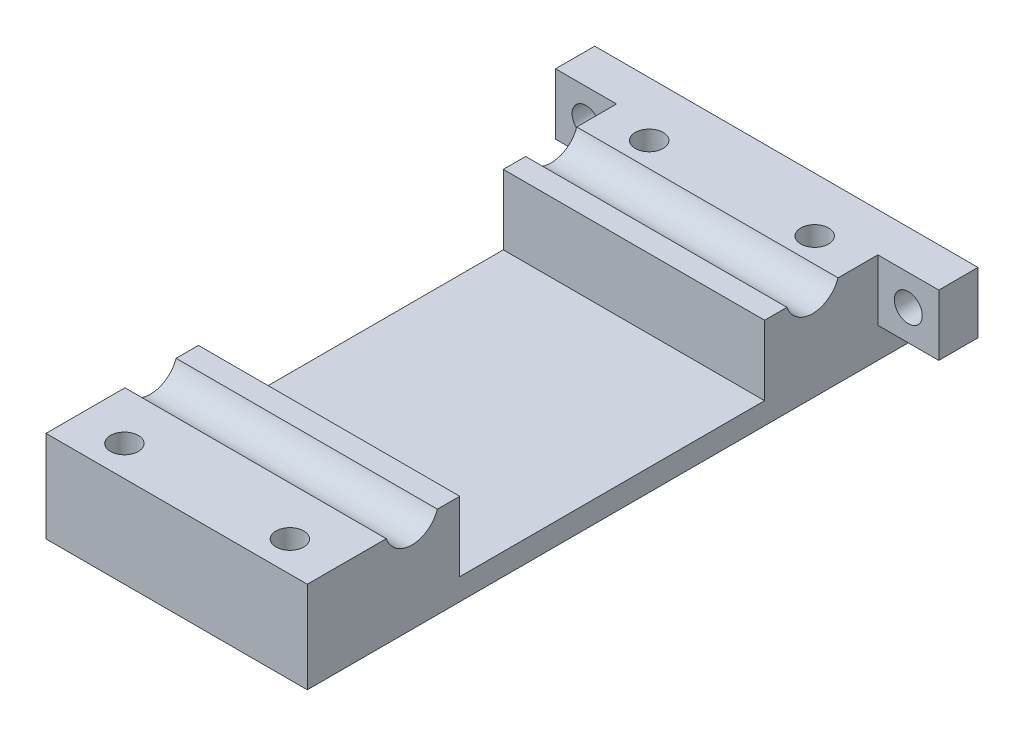
SolidWorks part; units mm, degrees
ref_plane "Front Plane" through (0, 0, 0) normal (0, 0, 1) x (1, 0, 0)
ref_plane "Top Plane" through (0, 0, 0) normal (0, 1, 0) x (1, 0, 0)
ref_plane "Right Plane" through (0, 0, 0) normal (1, 0, 0) x (0, 0, -1)
sketch "Sketch1" plane through (0, 0, 0) normal (0, 1, 0) x (1, 0, 0)
  line L1 (-15, -35) -> (15, -35)
  line L2 (-15, -35) -> (-15, 35)
  line L3 (-15, 35) -> (15, 35)
  line L4 (15, -35) -> (15, 35)
  line L5 (-15, -35) -> (15, 35) construction
  line L6 (-15, 35) -> (15, -35) construction
  point P0 (0, 0)
  dimension "D1" = 30
  dimension "D2" = 70
extrude "Boss-Extrude1" add sketch "Sketch1" along normal blind 10.5
sketch "Sketch2" plane through (0, 10.5, 0) normal (0, 1, 0) x (1, 0, 0)
  line L0 (15, -35) -> (15, 35) construction
  line L1 (-15, -17.5) -> (15, -17.5)
  line L2 (-15, -17.5) -> (-15, 17.5)
  line L3 (-15, 17.5) -> (15, 17.5)
  line L4 (15, -17.5) -> (15, 17.5)
  line L5 (-15, -17.5) -> (15, 17.5) construction
  line L6 (-15, 17.5) -> (15, -17.5) construction
  point P0 (0, 0)
  dimension "D1" = 35
extrude "Cut-Extrude1" cut sketch "Sketch2" against normal blind 8
sketch "Sketch3" plane through (15, 0, 0) normal (1, 0, 0) x (0, 0, -1)
  line L0 (-35, 10.5) -> (-17.5, 10.5) construction
  line L1 (-35, 10.5) -> (-35, 0) construction
  circle A0 centre (-23, 11.5) radius 3.1
  circle A1 centre (23, 11.5) radius 3.1
  point P4 (0, 0)
  dimension "D1" = 6.2
  dimension "D2" = 6.2
  dimension "D3" = 1
  dimension "D4" = 12
  dimension "D5" = 46
extrude "Cut-Extrude2" cut sketch "Sketch3" against normal through all
sketch "Sketch4" plane through (0, 10.5, 0) normal (0, 1, 0) x (1, 0, 0)
  line L0 (-15, 35) -> (-15, 25.9343) construction
  line L1 (15, 25.9343) -> (15, 35) construction
  line L2 (15, 35) -> (-15, 35) construction
  line L3 (-15, -35) -> (15, -35) construction
  circle A0 centre (-9.5, -31.5) radius 1.6
  circle A1 centre (9.5, -31.5) radius 1.6
  circle A2 centre (-9.5, 28.75) radius 1.6
  circle A3 centre (9.5, 28.75) radius 1.6
  point P8 (0, 0)
  point P9 (0, 0)
  point P10 (0, 0)
  point P19 (0, 0)
  dimension "D1" = 3.2
  dimension "D2" = 3.2
  dimension "D3" = 3.2
  dimension "D4" = 3.2
  dimension "D8" = 3.5
  dimension "D5" = 5.5
  dimension "D6" = 5.5
  dimension "D7" = 6.25
extrude "Cut-Extrude3" cut sketch "Sketch4" against normal through all
sketch "Sketch5" plane through (0, 0, -35) normal (0, 0, -1) x (-1, 0, 0)
  line L1 (15, 10.5) -> (22, 10.5)
  line L2 (15, 10.5) -> (15, 3.5)
  line L3 (15, 3.5) -> (22, 3.5)
  line L4 (22, 10.5) -> (22, 3.5)
  line L5 (-15, 10.5) -> (-22, 10.5)
  line L6 (-15, 10.5) -> (-15, 3.5)
  line L7 (-15, 3.5) -> (-22, 3.5)
  line L8 (-22, 10.5) -> (-22, 3.5)
  dimension "D1" = 7
  dimension "D2" = 7
  dimension "D3" = 7
  dimension "D4" = 7
extrude "Boss-Extrude2" add sketch "Sketch5" against normal blind 4.5
sketch "Sketch6" plane through (0, 0, -35) normal (0, 0, -1) x (-1, 0, 0)
  line L0 (22, 3.5) -> (22, 10.5) construction
  line L1 (15, 3.5) -> (22, 3.5) construction
  line L2 (-22, 10.5) -> (-22, 3.5) construction
  circle A0 centre (-18.5, 7) radius 1.6
  circle A1 centre (18.5, 7) radius 1.6
  point P4 (0, 0)
  dimension "D2" = 3.5
  dimension "D3" = 3.5
  dimension "D4" = 3.2
  dimension "D5" = 3.2
  dimension "D1" = 3.5
extrude "Cut-Extrude4" cut sketch "Sketch6" against normal up to next
